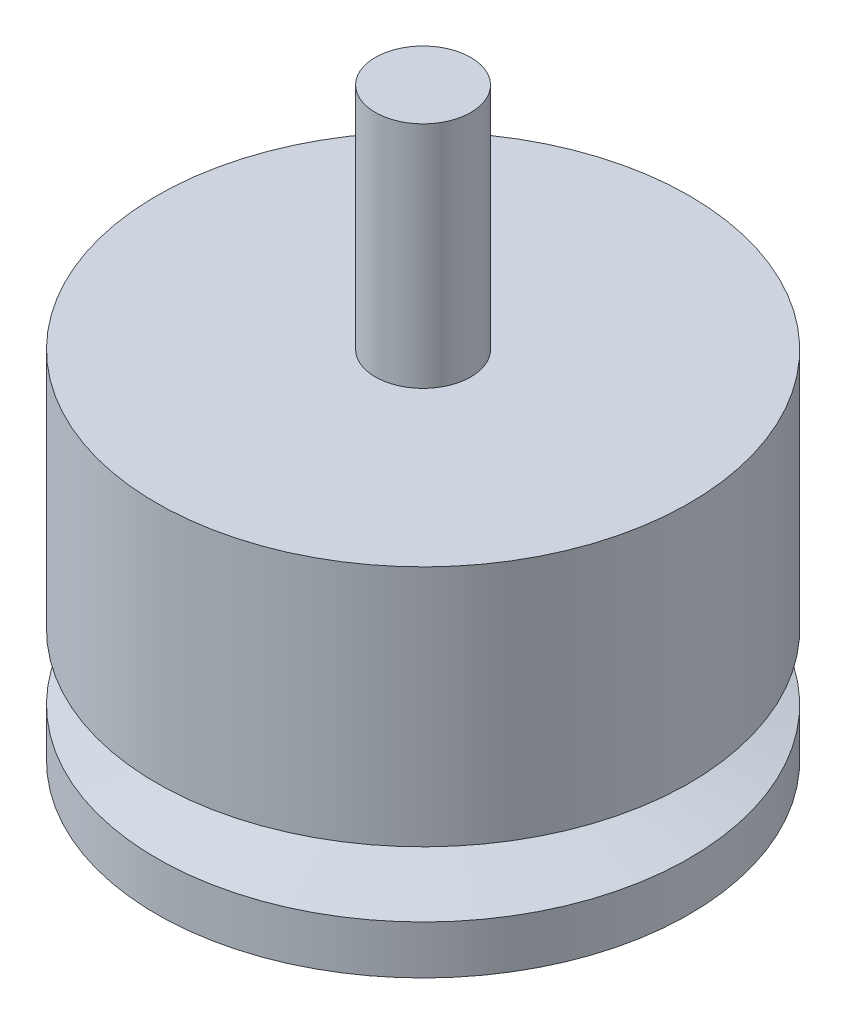
SolidWorks part; units mm, degrees
ref_plane "Front Plane" through (0, 0, 0) normal (0, 0, 1) x (1, 0, 0)
ref_plane "Top Plane" through (0, 0, 0) normal (0, 1, 0) x (1, 0, 0)
ref_plane "Right Plane" through (0, 0, 0) normal (1, 0, 0) x (0, 0, -1)
sketch "Sketch1" plane through (0, 0, 0) normal (0, 0, 1) x (1, 0, 0)
  line L0 (0, 0) -> (0, 4.929) construction
  line L1 (0, 0) -> (13.95, 0)
  line L2 (13.95, 0) -> (13.95, 18.65)
  line L3 (13.95, 18.65) -> (2.5, 18.65)
  line L4 (2.5, 30.65) -> (2.5, 18.65)
  line L5 (0, 30.65) -> (15.4757, 30.65) construction
  line L6 (0, 0) -> (0, 30.65)
  line L7 (0, 30.65) -> (2.5, 30.65)
  line L8 (13.95, 5.95) -> (2.54, 5.95)
  line L9 (2.54, 5.95) -> (2.54, 5.08)
  line L10 (2.54, 5.08) -> (13.95, 2.54)
  dimension "D1" = 13.95
  dimension "D2" = 5
  dimension "D3" = 12
  dimension "D4" = 2.54
  dimension "D5" = 30.65
  dimension "D6" = 12.7
  dimension "D7" = 2.54
  dimension "D8" = 5.08
revolve "Revolve1" add sketch "Sketch1" angle 360 about L0
sketch "Sketch2" plane through (0, 0, 0) normal (0, -1, 0) x (1, 0, 0)
  line L1 (-5.6569, -5.6569) -> (5.6569, -5.6569) construction
  line L2 (-5.6569, -5.6569) -> (-5.6569, 5.6569) construction
  line L3 (-5.6569, 5.6569) -> (5.6569, 5.6569) construction
  line L4 (5.6569, -5.6569) -> (5.6569, 5.6569) construction
  line L5 (-5.6569, -5.6569) -> (5.6569, 5.6569) construction
  line L6 (-5.6569, 5.6569) -> (5.6569, -5.6569) construction
  point P0 (0, 0)
  dimension "D1" = 16
hole_wizard "M3.5x0.6 Tapped Hole1" positions "3DSketch1" profile "Sketch4" tap size "M3.5x0.6" standard "ANSI Metric"
sketch3d "3DSketch1"
  point P0 (-5.6569, 0, 5.6569)
  point P3 (5.6569, 0, 5.6569)
  point P6 (5.6569, 0, -5.6569)
  point P9 (-5.6569, 0, -5.6569)
sketch "Sketch4" plane through (-5.6569, 0, 5.6569) normal (1, 0, 0) x (0, 0, -1)
  line L0 (0, 0) -> (0, 4.9352)
  line L1 (0, 4.9352) -> (1.45, 4.064)
  line L2 (1.45, 4.064) -> (1.45, 0)
  line L5 (1.45, 0) -> (0, 0)
  line L10 (0, 4.9352) -> (-1.45, 4.064) construction
  line L11 (0, -6.35) -> (0, 107.95) construction
  dimension "Tap Drill Dia." = 2.9
  dimension "Tap Drill Depth" = 4.064
  dimension "Drill Angle" = 118
cosmetic thread "Hole Thread1" parameters "D1"=2.286, "D2"=3.5
cosmetic thread "Hole Thread2" parameters "D1"=2.286, "D2"=3.5
cosmetic thread "Hole Thread3" parameters "D1"=2.286, "D2"=3.5
cosmetic thread "Hole Thread4" parameters "D1"=2.286, "D2"=3.5
